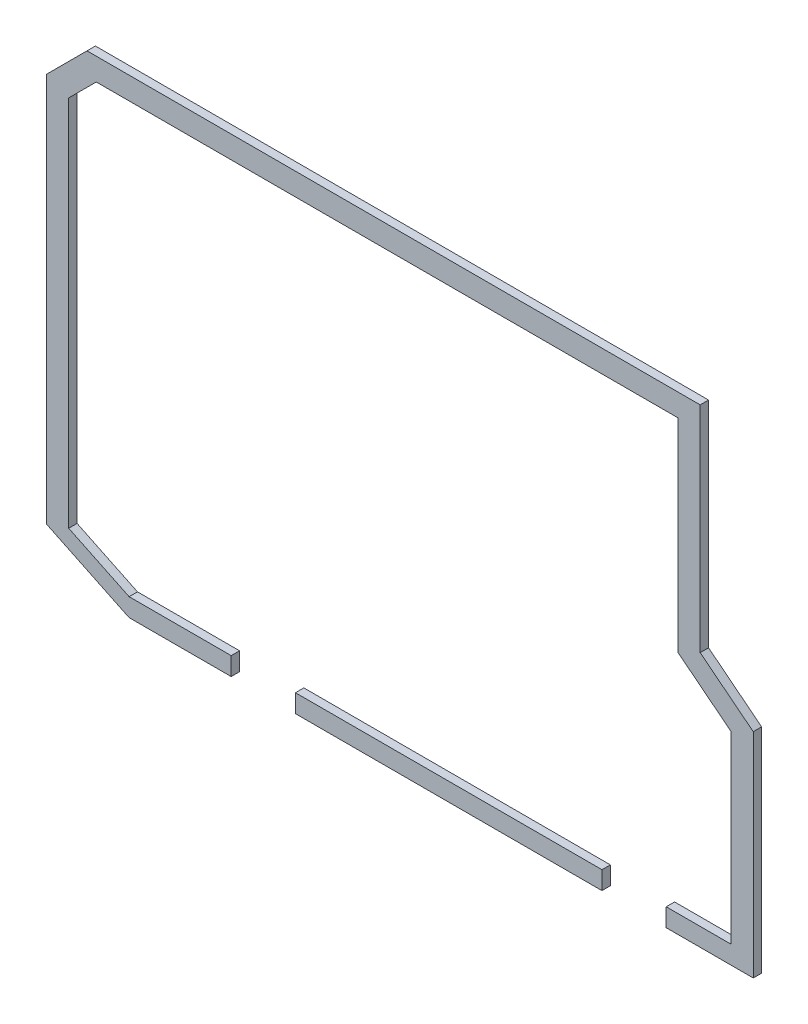
SolidWorks part; units mm, degrees
ref_plane "Plan de face" through (0, 0, 0) normal (0, 0, 1) x (1, 0, 0)
ref_plane "Plan de dessus" through (0, 0, 0) normal (0, 1, 0) x (1, 0, 0)
ref_plane "Plan de droite" through (0, 0, 0) normal (1, 0, 0) x (0, 0, -1)
sketch "Esquisse1" plane through (0, 0, 0) normal (0, 0, 1) x (1, 0, 0)
  line L0 (468.5, 23) -> (468.5, 175.6922)
  line L1 (468.5, 175.6922) -> (430.5, 205.6922)
  line L2 (430.5, 205.6922) -> (430.5, 359.3)
  line L3 (430.5, 359.3) -> (-8.3995, 359.3)
  line L4 (-8.3995, 359.3) -> (-37.5, 330.1995)
  line L5 (-37.5, 330.1995) -> (-37.5, 51.475)
  line L6 (452.5, 36) -> (452.5, 167.9386)
  line L7 (452.5, 167.9386) -> (414.5, 197.9386)
  line L8 (-5.0858, 351.3) -> (-29.5, 326.8858)
  line L9 (-29.5, 326.8858) -> (-29.5, 47.6288)
  line L10 (-29.5, 47.6288) -> (21.7279, 23)
  line L11 (21.7279, 23) -> (460.5, 23)
  line L12 (460.5, 23) -> (460.5, 171.8154)
  line L13 (460.5, 171.8154) -> (422.5, 201.8154)
  line L14 (422.5, 201.8154) -> (422.5, 351.3)
  line L15 (422.5, 351.3) -> (-5.0858, 351.3)
  line L16 (-5.0858, 351.3) -> (-29.5, 326.8858) construction
  line L17 (-29.5, 326.8858) -> (-29.5, 47.6288) construction
  line L18 (-29.5, 47.6288) -> (21.7279, 23)
  line L19 (21.7279, 23) -> (94.8, 23)
  line L20 (460.5, 23) -> (460.5, 171.8154) construction
  line L21 (460.5, 171.8154) -> (422.5, 201.8154) construction
  line L22 (422.5, 201.8154) -> (422.5, 351.3) construction
  line L23 (422.5, 351.3) -> (-5.0858, 351.3) construction
  line L24 (414.5, 197.9386) -> (414.5, 343.3)
  line L25 (414.5, 343.3) -> (-1.7721, 343.3)
  line L26 (-1.7721, 343.3) -> (-21.5, 323.5721)
  line L27 (-21.5, 323.5721) -> (-21.5, 56.7826)
  line L28 (94.8, 36) -> (21.7279, 36)
  line L29 (21.7279, 36) -> (-21.5, 56.7826)
  line L30 (-29.5, 47.6288) -> (-37.5, 51.475)
  line L31 (94.8, 36) -> (94.8, 23)
  line L32 (-37.5, 330.1995) -> (-37.5, 47.6288) construction
  line L33 (-21.5, 323.5721) -> (-21.5, 47.6288) construction
  line L34 (140.8, 23) -> (140.8, 36)
  line L35 (140.8, 36) -> (360.2, 36)
  line L36 (360.2, 36) -> (360.2, 23)
  line L37 (140.8, 23) -> (360.2, 23)
  line L38 (406.2, 23) -> (406.2, 36)
  line L39 (406.2, 36) -> (452.5, 36)
  line L40 (406.2, 23) -> (460.5, 23)
  line L41 (452.5, 23) -> (452.5, 167.9386) construction
  line L42 (460.5, 23) -> (468.5, 23)
  dimension "D1" = 0
  dimension "D2" = 8
  dimension "D3" = 8
extrude "Boss.-Extru.1" add sketch "Esquisse1" along normal blind 6
